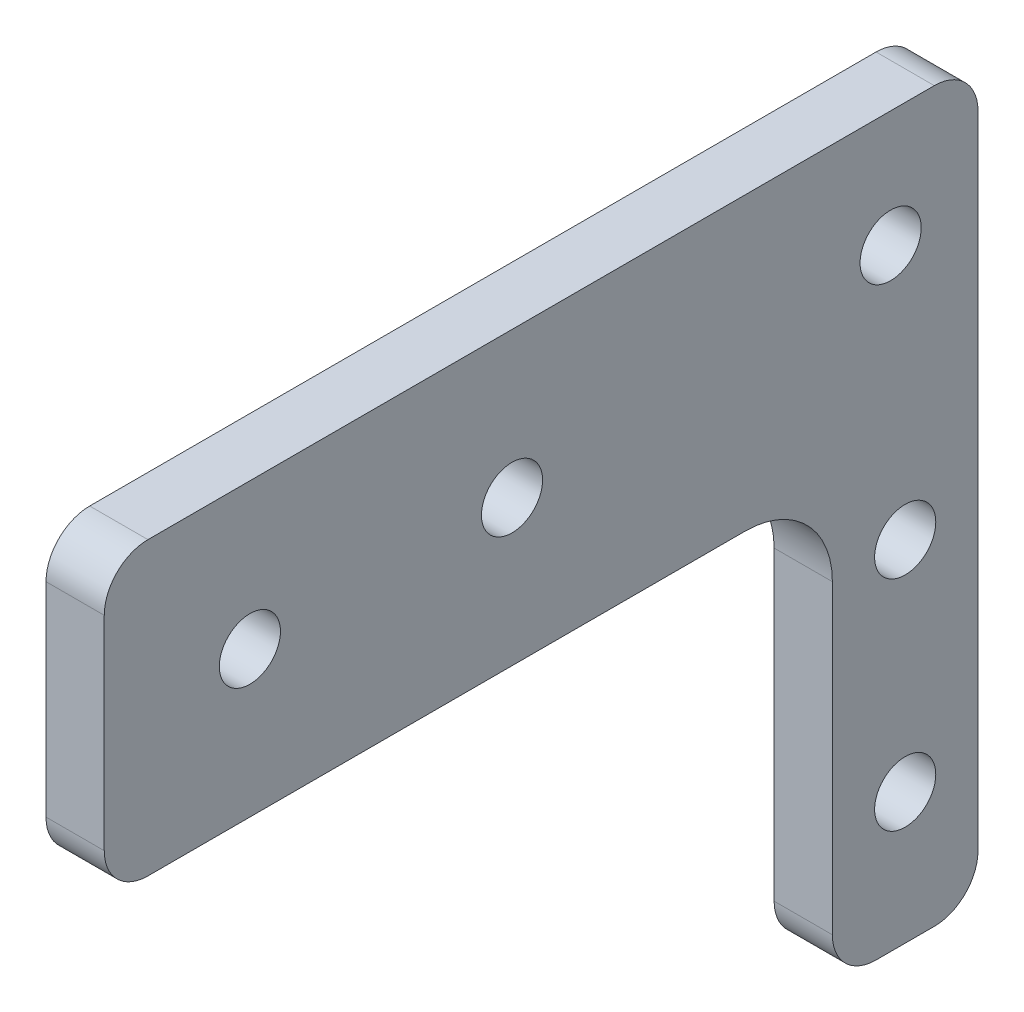
SolidWorks part; units mm, degrees
ref_plane "前视基准面" through (0, 0, 0) normal (0, 0, 1) x (1, 0, 0)
ref_plane "上视基准面" through (0, 0, 0) normal (0, 1, 0) x (1, 0, 0)
ref_plane "右视基准面" through (0, 0, 0) normal (1, 0, 0) x (0, 0, -1)
sketch "草图2" plane through (0, 0, 0) normal (1, 0, 0) x (0, 0, -1)
  line L0 (-211.25, 80.0417) -> (-157.25, 80.0417)
  line L1 (-154.25, 77.0417) -> (-154.25, 33.0417)
  line L2 (-157.25, 30.0417) -> (-161.25, 30.0417)
  line L3 (-164.25, 33.0417) -> (-164.25, 54.0417)
  line L4 (-170.25, 60.0417) -> (-211.25, 60.0417)
  line L5 (-214.25, 63.0417) -> (-214.25, 77.0417)
  arc A0 (-164.25, 54.0417) -> (-170.25, 60.0417) centre (-170.25, 54.0417) ccw
  arc A1 (-157.25, 80.0417) -> (-154.25, 77.0417) centre (-157.25, 77.0417) cw
  arc A2 (-214.25, 63.0417) -> (-211.25, 60.0417) centre (-211.25, 63.0417) ccw
  arc A3 (-214.25, 77.0417) -> (-211.25, 80.0417) centre (-211.25, 77.0417) cw
  arc A4 (-161.25, 30.0417) -> (-164.25, 33.0417) centre (-161.25, 33.0417) cw
  arc A5 (-157.25, 30.0417) -> (-154.25, 33.0417) centre (-157.25, 33.0417) ccw
  point P10 (-154.25, 80.0417)
  point P13 (-214.25, 60.0417)
  point P16 (-214.25, 80.0417)
  point P19 (-164.25, 30.0417)
  point P22 (-154.25, 30.0417)
  dimension "D5" = 6
  dimension "D6" = 3
  dimension "D7" = 3
  dimension "D8" = 3
  dimension "D1" = 60
  dimension "D2" = 50
  dimension "D3" = 10
  dimension "D4" = 20
extrude "凸台-拉伸1" add sketch "草图2" along normal blind 4
sketch "草图3" plane through (4, 0, 0) normal (1, 0, 0) x (0, 0, -1)
  line L0 (-159.25, 80.0417) -> (-159.25, 54.0417) construction
  line L1 (-157.25, 80.0417) -> (-211.25, 80.0417) construction
  line L2 (-159.25, 54.0417) -> (-159.25, 39.0417) construction
  line L3 (-154.25, 33.0417) -> (-154.25, 77.0417) construction
  line L5 (-214.25, 70.0417) -> (-204.25, 70.0417) construction
  line L6 (-214.25, 77.0417) -> (-214.25, 63.0417) construction
  line L7 (-204.25, 70.0417) -> (-186.25, 70.0417) construction
  circle A1 centre (-204.25, 70.0417) radius 2.1
  circle A2 centre (-186.25, 70.0417) radius 2.1
  circle A3 centre (-159.25, 54.0417) radius 2.1
  circle A4 centre (-159.25, 39.0417) radius 2.1
  circle A6 centre (-160.25, 72.0417) radius 2.1
  dimension "D7" = 4.2
  dimension "D8" = 4.2
  dimension "D9" = 4.2
  dimension "D10" = 4.2
  dimension "D11" = 4.2
  dimension "D12" = 6
  dimension "D3" = 10
  dimension "D4" = 18
  dimension "D5" = 15
  dimension "D6" = 26
  dimension "8" = 8
extrude "切除-拉伸1" cut sketch "草图3" against normal blind 10
equation "\"4。2\"=14.6455"
